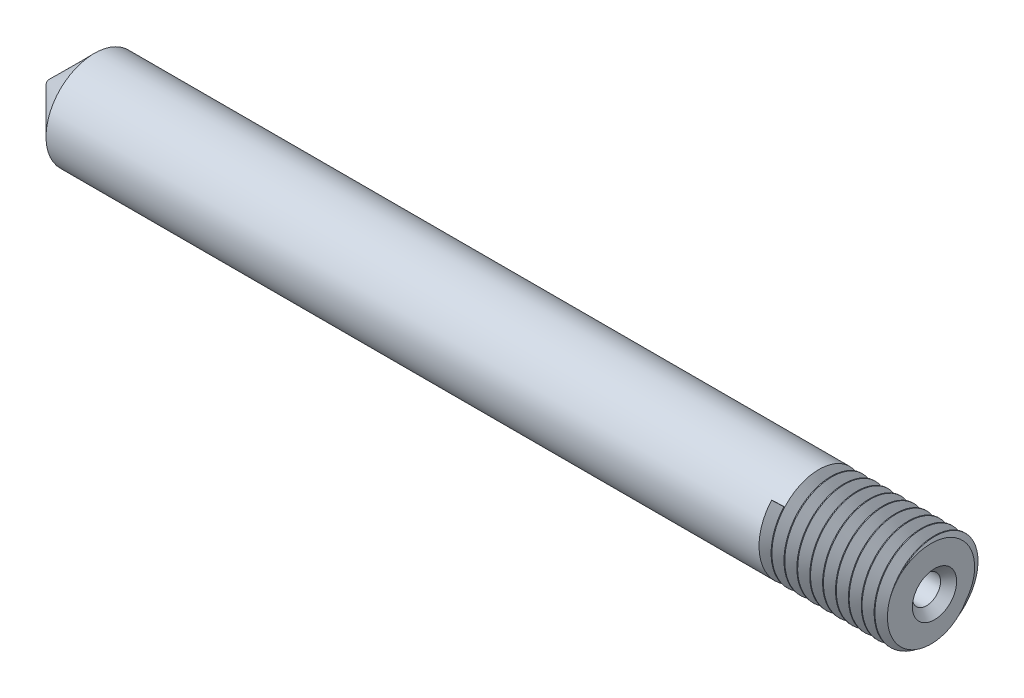
SolidWorks part; units mm, degrees
material "1.4306 (X2CrNi19-11)"
ref_plane "Piano frontale" through (0, 0, 0) normal (0, 0, 1) x (1, 0, 0)
ref_plane "Piano superiore" through (0, 0, 0) normal (0, 1, 0) x (1, 0, 0)
ref_plane "Piano destro" through (0, 0, 0) normal (1, 0, 0) x (0, 0, -1)
sketch "Schizzo3" plane through (0, 0, 0) normal (0, 1, 0) x (1, 0, 0)
  line L0 (0, 3) -> (0, 0.875)
  line L1 (0, 0.875) -> (-52.3309, 0.875)
  line L2 (-52.3309, 0.875) -> (-53.5, 0.2)
  line L3 (-53.5, 0.2) -> (-55, 0.2)
  line L4 (-55, 0.2) -> (-52.2, 3)
  line L5 (-52.2, 3) -> (0, 3)
  line L6 (0, 0) -> (-52.6016, 0) construction
  dimension "D1" = 55
  dimension "D2" = 0.2
  dimension "D3" = 1.5
  dimension "D4" = 1.75
  dimension "D5" = 3
  dimension "D6" = 30
  dimension "D7" = 45
revolve "Rivoluzione1" add sketch "Schizzo3" angle 360 about L6
chamfer "Smusso1" distance 0.5 angle 45 1 edges at (0, 0, -0.875)
sketch "Schizzo6" plane through (0, 0, 0) normal (1, 0, 0) x (0, 0, -1)
  circle A0 centre (0, 0) radius 3
curve "Elica/Spirale1" pitch 0.8 height 8 turns 10
ref_plane "Piano1" through (0, 2.1213, 2.1213) normal (-0.0424, 0.7065, -0.7065) x (0.9991, 0.03, -0.03)
sketch "Schizzo8" plane through (0, 2.1213, 2.1213) normal (-0.0424, 0.7065, -0.7065) x (0.9991, 0.03, -0.03)
  line L0 (0.75, -0.0006) -> (1.125, 0.6489) construction
  line L1 (1.125, 0.6489) -> (-0.375, 0.6489) construction
  line L2 (0.375, 0.6489) -> (0.75, -0.0006)
  line L3 (1.5, -0.005) -> (1.5, -0.1963) construction
  line L4 (0.375, 0.6489) -> (0.375, 0.2006) construction
  line L5 (-0.75, -0.005) -> (-0.75, -0.1963) construction
  line L6 (0.375, 0.6489) -> (0, -0.0006)
  line L7 (0, -0.0006) -> (-0.375, 0.6489) construction
  line L8 (0, -0.0006) -> (0.75, -0.0006)
  dimension "D1" = 30
  dimension "D2" = 30
  dimension "D3" = 0.75
sweep "Taglia-Sweep13" cut profiles "Schizzo8" path "Elica/Spirale1"
